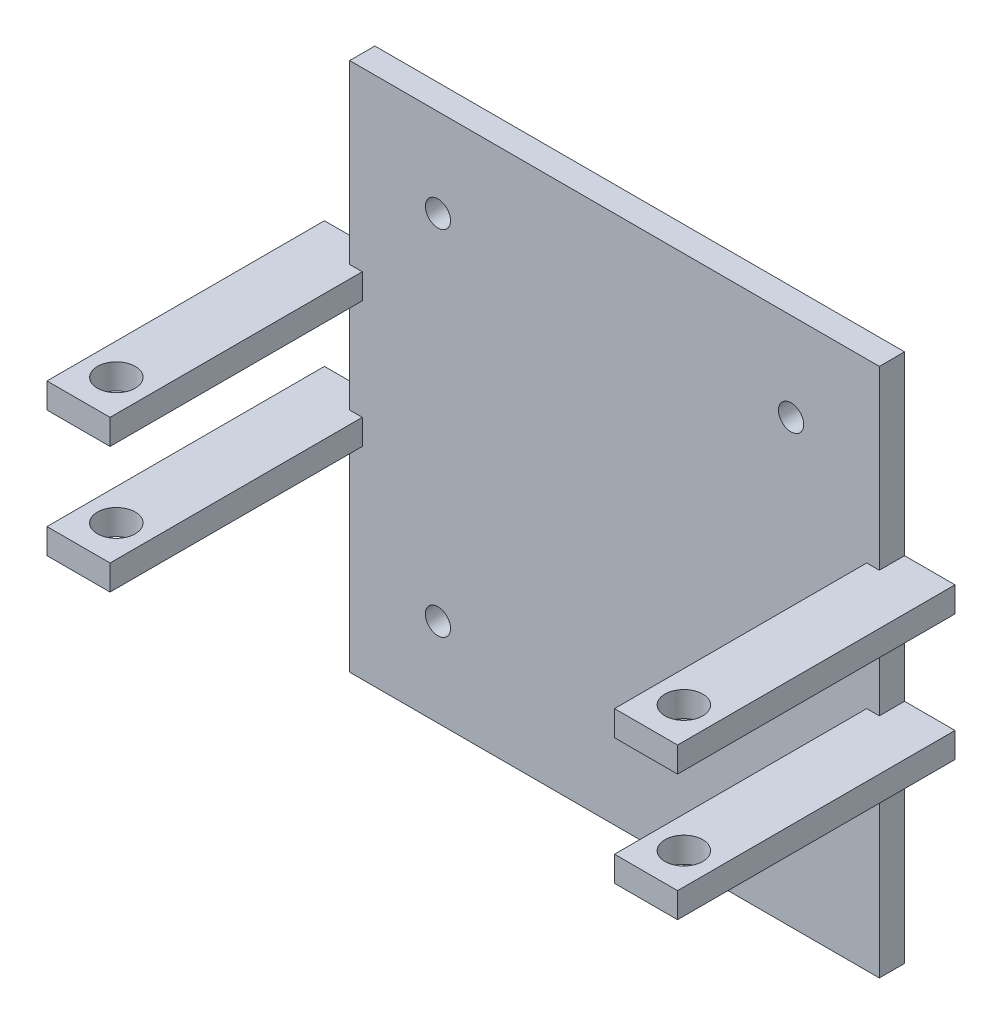
SolidWorks part; units mm, degrees
ref_plane "前视基准面" through (0, 0, 0) normal (0, 0, 1) x (1, 0, 0)
ref_plane "上视基准面" through (0, 0, 0) normal (0, 1, 0) x (1, 0, 0)
ref_plane "右视基准面" through (0, 0, 0) normal (1, 0, 0) x (0, 0, -1)
sketch "草图1" plane through (0, 0, 0) normal (0, 0, 1) x (1, 0, 0)
  line L1 (-21.8386, 17.8533) -> (20.1614, 17.8533)
  line L2 (-21.8386, 17.8533) -> (-21.8386, -24.1467)
  line L3 (-21.8386, -24.1467) -> (20.1614, -24.1467)
  line L4 (20.1614, 17.8533) -> (20.1614, -24.1467)
  dimension "D1" = 42
  dimension "D2" = 42
extrude "凸台-拉伸1" add sketch "草图1" along normal blind 2
sketch "草图2" plane through (0, 0, 2) normal (0, 0, 1) x (1, 0, 0)
  line L0 (-21.8386, 17.8533) -> (-21.8386, -24.1467) construction
  line L1 (20.1614, 17.8533) -> (-21.8386, 17.8533) construction
  circle A0 centre (-14.8386, 10.8533) radius 1
  dimension "D1" = 7
  dimension "D2" = 7
extrude "切除-拉伸2" cut sketch "草图2" against normal through all
pattern_linear "阵列(线性)1" count 2 spacing 28 along (0, -1, 0) count 2 spacing 28 along (1, 0, 0) of "切除-拉伸2"
sketch "草图4" plane through (0, 0, 2) normal (0, 0, 1) x (1, 0, 0)
  line L0 (-21.8386, 17.8533) -> (-21.8386, -24.1467) construction
  line L1 (-25.8386, 3.8533) -> (24.1614, 3.8533)
  line L2 (-25.8386, 3.8533) -> (-25.8386, 1.8533)
  line L3 (-25.8386, 1.8533) -> (24.1614, 1.8533)
  line L4 (24.1614, 3.8533) -> (24.1614, 1.8533)
  line L5 (20.1614, 17.8533) -> (-21.8386, 17.8533) construction
  dimension "D1" = 50
  dimension "D2" = 2
  dimension "D3" = 4
  dimension "D4" = 14
extrude "凸台-拉伸2" add sketch "草图4" along normal blind 20 and the other way up to vertex (2 mm away) contours L1 L4 L3 L2
sketch "草图7" plane through (0, 0, 22) normal (0, 0, 1) x (1, 0, 0)
  line L0 (-21.8386, 3.8533) -> (20.1614, 3.8533) construction
  line L1 (-20.8386, 3.8533) -> (19.1614, 3.8533)
  line L2 (-20.8386, 3.8533) -> (-20.8386, 1.8533)
  line L3 (-20.8386, 1.8533) -> (19.1614, 1.8533)
  line L4 (19.1614, 3.8533) -> (19.1614, 1.8533)
  line L5 (-25.8386, 1.8533) -> (24.1614, 1.8533) construction
  line L6 (-25.8386, 3.8533) -> (-25.8386, 1.8533) construction
  dimension "D1" = 40
  dimension "D2" = 5
extrude "切除-拉伸3" cut sketch "草图7" against normal up to surface (20 mm away) up to face at (14.1614, 10.8533, 2)
pattern_linear "阵列(线性)2" count 2 spacing 10 along (0, -1, 0) of "凸台-拉伸2", "切除-拉伸3"
sketch "草图8" plane through (0, 3.8533, 0) normal (0, 1, 0) x (1, 0, 0)
  line L0 (-21.8386, -2) -> (-21.8386, 0) construction
  line L2 (-25.8386, 0) -> (-21.8386, 0) construction
  circle A0 centre (-23.3386, -19) radius 1.5
  dimension "D2" = 3
  dimension "D1" = 1.5
  dimension "D3" = 19
extrude "切除-拉伸4" cut sketch "草图8" against normal through all contours A0
pattern_linear "阵列(线性)3" count 4 spacing 5 along (0, 0, 1) count 2 spacing 45 along (1, 0, 0) of "切除-拉伸4"
